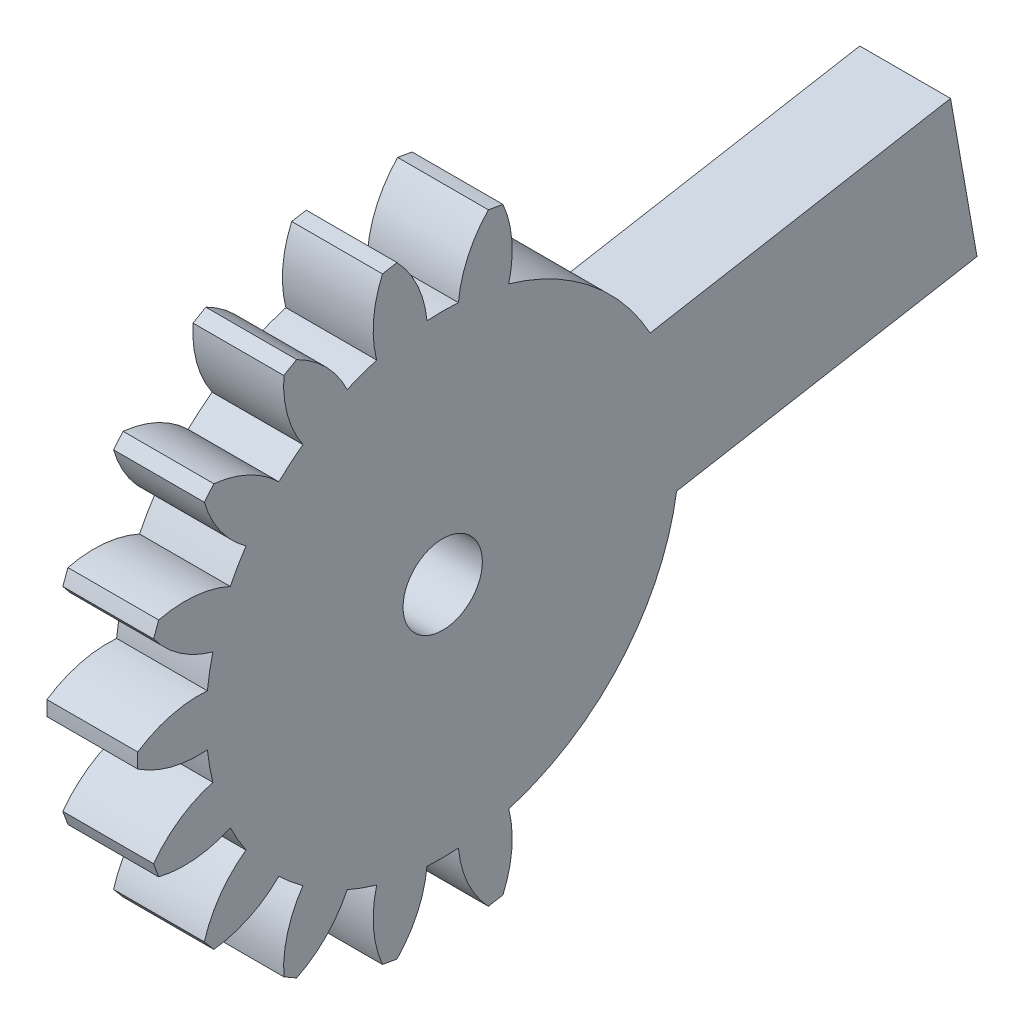
SolidWorks part; units mm, degrees
ref_plane "Plane1" through (0, 0, 0) normal (0, 0, 1) x (1, 0, 0)
ref_plane "Plane2" through (0, 0, 0) normal (0, 1, 0) x (1, 0, 0)
ref_plane "Plane3" through (0, 0, 0) normal (1, 0, 0) x (0, 0, -1)
sketch "HoldingSke" plane through (0, 0, 0) normal (0, 1, 0) x (1, 0, 0)
  line L0 (0, 0) -> (483.1367, -156.9806)
  line L1 (-15, 0) -> (100, 0) construction
  line L2 (0, 0) -> (-2.1039, 2.3779)
  line L3 (0, 0) -> (-11.863, 4.5341)
  line L4 (0, 0) -> (8.2133, 2.6687)
  line L5 (0, 0) -> (-47.5972, -17.7524)
  line L6 (0, 0) -> (-2.632, -1.7758)
  line L7 (-2.1039, 2.3779) -> (8.8308, 51.9871)
  line L8 (-76.2, 54.61) -> (-72.771, 54.61)
  line L9 (-71.009, 38.7566) -> (-53.1078, 45.2721)
  line L10 (-76.2, 71.12) -> (104.1128, 71.12)
  line L11 (0, 0) -> (-3.175, 0)
  line L12 (-76.2, 101.6) -> (-76.1492, 101.6)
  line L13 (24.9733, 27.94) -> (52.9518, 28.4284)
  line L14 (24.9733, 27.94) -> (25.0241, 27.9398)
  line L15 (24.9733, 27.94) -> (100.4021, 29.52)
  circle A0 centre (0, 0) radius 1.5875
  circle A1 centre (0, 0) radius 9.8552
  circle A2 centre (0, 0) radius 38.1
  circle A3 centre (0, 0) radius 1.5875
  dimension "MHD" = 19.7104
  dimension "Hub_dia" = 76.2
  dimension "Bore" = 3.175
  dimension "MBD" = 3.175
  dimension "Num_teeth" = 18
  dimension "Pitch_radius" = 180.3128
  dimension "Pitch" = 508
  dimension "Width" = 3.175
  dimension "Overall_len" = 50.8
  dimension "Show_teeth" = 18
  dimension "Thickness" = 3.175
  dimension "OAL" = 50.8001
  dimension "T_dim" = 3.429
  dimension "Ap" = 20
  dimension "H" = 19.05
  dimension "Backlash" = 0.0508
  dimension "Addendum_fac" = 1
  dimension "Dedendum_fac" = 1.2
  dimension "Clearance_fac" = 0.2
  dimension "Dedendum_add" = 0.0508
sketch "BasProSke" plane through (0, 0, 0) normal (0, 1, 0) x (1, 0, 0)
  line L0 (-10, 0) -> (60, 0) construction
  line L1 (0, 0) -> (0, 12.7)
  line L2 (0, 0) -> (3.175, 0)
  line L3 (3.175, 0) -> (3.175, 12.7)
  line L4 (3.175, 12.7) -> (0, 12.7)
  dimension "Diameter" = 25.4
  dimension "Thickness" = 3.175
revolve "Base-Revolve" add sketch "BasProSke" angle 360 about L0
sketch "TooCutSke" plane through (0, 0, 0) normal (1, 0, 0) x (0, 0, -1)
  line L1 (0, 0) -> (0, 107) construction
  line L2 (0, 0) -> (-1.085, 11.3784) construction
  line L3 (0, 0) -> (-3.9571, 22.4417) construction
  line L4 (-1.085, 11.3784) -> (-1.9785, 11.2208) construction
  arc A0 (0.6537, 9.8335) -> (-0.6537, 9.8335) centre (0, 0) ccw
  arc A1 (1.9234, 12.5792) -> (-1.9234, 12.5792) centre (0, 0) ccw
  circle A2 centre (0, 0) radius 11.43 construction
  circle A3 centre (0, 0) radius 10.7407 construction
  arc A4 (-0.6537, 9.8335) -> (-1.9234, 12.5792) centre (-5.2046, 9.3954) ccw
  arc A5 (1.9234, 12.5792) -> (0.6537, 9.8335) centre (5.2046, 9.3954) ccw
  dimension "Root_dia" = 19.7104
  dimension "Overcut_dia" = 25.4508
  dimension "Pitch_dia" = 22.86
  dimension "Base_dia" = 21.4814
  dimension "Flank_rad" = 4.572
  dimension "Half_ang" = 10
  dimension "Half_CT" = 0.9073
extrude "ToothCut" cut sketch "TooCutSke" along normal through all
fillet "Breaks" [suppressed] radius 0.0254
fillet "RootFillets" [suppressed] radius 0.3048
pattern_circular "TeethCuts" count 18 every 20 about axis through (-10, 0, 0) along (1, 0, 0) of "ToothCut", "RootFillets", "Breaks"
sketch "HubNeaOneSke" plane through (0, 0, 0) normal (-1, 0, 0) x (0, 0, 1)
  circle A0 centre (0, 0) radius 9.8552
  dimension "Diameter" = 19.7104
extrude "HubNearOne" [suppressed] add sketch "HubNeaOneSke" along normal blind 47.6251
sketch "HubNeaBotSke" plane through (0, 0, 0) normal (-1, 0, 0) x (0, 0, 1)
  circle A0 centre (0, 0) radius 9.8552
  dimension "Diameter" = 19.7104
extrude "HubNearBoth" [suppressed] add sketch "HubNeaBotSke" along normal blind 23.8125
ref_plane "FarPln" through (3.175, 0, 0) normal (1, 0, 0) x (0, 0, -1)
sketch "HubFarSke" plane through (3.175, 0, 0) normal (1, 0, 0) x (0, 0, -1)
  circle A0 centre (0, 0) radius 9.8552
  dimension "Diameter" = 19.7104
extrude "HubFar" [suppressed] add sketch "HubFarSke" along normal blind 23.8125
sketch "BorSke" plane through (0, 0, 0) normal (1, 0, 0) x (0, 0, -1)
  circle A0 centre (0, 0) radius 1.5875
  dimension "Diameter" = 3.175
extrude "Bore" cut sketch "BorSke" along normal mid plane 101.6001
sketch "KeySke" plane through (0, 0, 0) normal (1, 0, 0) x (0, 0, -1)
  line L0 (-0.127, 0) -> (-0.127, 1.8415)
  line L1 (-0.127, 1.8415) -> (0.127, 1.8415)
  line L2 (0.127, 1.8415) -> (0.127, 0)
  line L3 (0, 0) -> (0, 34) construction
  line L4 (-0.127, 0) -> (0.127, 0)
  dimension "Offset" = 1.8415
  dimension "Width" = 0.254
extrude "Keyway" [suppressed] cut sketch "KeySke" along normal mid plane 101.6001
pattern_circular "Keyway2" [suppressed] count 2 every 90 about axis through (-10, 0, 0) along (1, 0, 0)
sketch "Sketch3" plane through (0, 0, 0) normal (-1, 0, 0) x (0, 0, 1)
  line L0 (2.2053, 12.5071) -> (-2.2053, -12.5071) construction
  arc A0 (2.5076, 12.45) -> (1.9018, 12.5568) centre (0, 0) ccw construction
  arc A1 (-2.5076, -12.45) -> (-1.9018, -12.5568) centre (0, 0) ccw construction
sketch "Sketch7" plane through (0, 0, 0) normal (-1, 0, 0) x (0, 0, 1)
  line L0 (-8.6367, 4.7469) -> (-21.1437, 6.9522)
  line L1 (-2.8893, 9.4221) -> (-3.6524, 12.8049)
  line L3 (-3.1735, -9.3303) -> (-4.1021, -12.668)
  line L4 (-21.1437, 6.9522) -> (-22.2464, 0.6987)
  line L5 (-22.2464, 0.6987) -> (-9.7393, -1.5067)
  line L6 (2.2053, 12.5071) -> (-2.2053, -12.5071) construction
  line L8 (0.5606, -0.0988) -> (50.9626, -8.9861) construction
  circle A1 centre (0, 0) radius 9.8552 construction
  arc A2 (-3.1735, -9.3303) -> (-9.7393, -1.5067) centre (0, 0) cw
  circle A3 centre (0, 0) radius 13.3156 construction
  arc A4 (-3.6524, 12.8049) -> (-4.1021, -12.668) centre (0, 0) cw
  arc A5 (-2.8893, 9.4221) -> (-8.6367, 4.7469) centre (0, 0) ccw
  arc A6 (0.6537, 9.8335) -> (-0.6537, 9.8335) centre (0, 0) ccw construction
  circle A7 centre (0, 0) radius 1.5875 construction
  arc A8 (-2.749, 9.464) -> (-3.9775, 9.0169) centre (0, 0) ccw construction
  point P29 (-21.6951, 3.8254)
  dimension "D1" = 6.35
  dimension "D7" = 26.6313
  dimension "D2" = 12.7
  dimension "D3" = 84.453
extrude "Cut-Extrude-Thin1" cut sketch "Sketch7" against normal blind 5.08 and the other way blind 1 thin
sketch "Sketch8" plane through (0, 0, 0) normal (-1, 0, 0) x (0, 0, 1)
  line L0 (-21.1437, 6.9522) -> (-22.2464, 0.6987)
  line L1 (-21.1437, 6.9522) -> (-8.6367, 4.7469)
  line L2 (-22.2464, 0.6987) -> (-9.7393, -1.5067)
  line L3 (-8.6367, 4.7469) -> (-9.7393, -1.5067)
  arc A0 (-2.749, 9.464) -> (-8.8429, 4.3507) centre (0, 0) ccw construction
extrude "Boss-Extrude1" add sketch "Sketch8" against normal up to surface (3.175 mm away) up to face at (3.175, 0.2886, 2.9794)
sketch "Sketch9" plane through (0, 0, 0) normal (-1, 0, 0) x (0, 0, 1)
  circle A1 centre (0, 0) radius 1.651
  dimension "D1" = 3.302
extrude "Cut-Extrude2" cut sketch "Sketch9" against normal up to surface (3.175 mm away)
scale "Scale1" bodies to scale 113 scale about centroid uniform scaling no x scale factor 1 y scale factor 0.84 z scale factor 0.84
equation "' \"Pitch@HoldingSke\" = 4"
equation "' \"Num_teeth@HoldingSke\" = 12"
equation "' \"Ap@HoldingSke\" =  20"
equation "' \"Width@HoldingSke\" = 0.5"
equation "' \"Hub_dia@HoldingSke\"= 1"
equation "' \"Overall_len@HoldingSke\" = 1.0"
equation "' \"Bore@HoldingSke\" = 0.75"
equation "' \"T_dim@HoldingSke\" = 0.85"
equation "' \"Width@KeySke\" = 0.25"
equation "' \"Show_teeth@HoldingSke\" = 13"
equation "' \"Backlash@HoldingSke\" = 0.009"
equation "' \"Addendum_fac@HoldingSke\" = 1.0"
equation "' \"Dedendum_fac@HoldingSke\" = 1.25"
equation "' \"Dedendum_add@HoldingSke\" = 0.00005"
equation "' \"Clearance_fac@HoldingSke\" = 0.25"
equation "' \"Pitch@HoldingSke\" = 0.5"
equation "' \"Num_teeth@HoldingSke\" = 23"
equation "' \"Show_teeth@HoldingSke\" = 23"
equation "' \"Backlash@HoldingSke\" = 0.0375"
equation "\"Overcut_dia@TooCutSke\" = (\"Num_teeth@HoldingSke\" + 2 * \"Addendum_fac@HoldingSke\") / \"Pitch@HoldingSke\" + 0.002"
equation "\"Pitch_dia@TooCutSke\" = \"Num_teeth@HoldingSke\" / \"Pitch@HoldingSke\""
equation "\"Base_dia@TooCutSke\" = \"Num_teeth@HoldingSke\" / \"Pitch@HoldingSke\" * cos((\"Ap@HoldingSke\"  * 3.14159265 / 180))"
equation "\"Root_dia@TooCutSke\" = (\"Num_teeth@HoldingSke\" + 2) / \"Pitch@HoldingSke\" - 2 * (\"Addendum_fac@HoldingSke\" + \"Dedendum_fac@HoldingSke\") / \"Pitch@HoldingSke\" - \"Dedendum_add@HoldingSke\" * 2"
equation "\"Half_ang@TooCutSke\" = 180 / \"Num_teeth@HoldingSke\""
equation "\"Half_CT@TooCutSke\" = \"Num_teeth@HoldingSke\" / \"Pitch@HoldingSke\" * sin((3.14159265 / 2 / \"Num_teeth@HoldingSke\")) / 2 - 7 * \"Backlash@HoldingSke\" / 4"
equation "\"Flank_rad@TooCutSke\" = \"Num_teeth@HoldingSke\" / \"Pitch@HoldingSke\" / 5"
equation "\"Radius@RootFillets\" = \"Clearance_fac@HoldingSke\" / \"Pitch@HoldingSke\" + \"Dedendum_add@HoldingSke\""
equation "\"Break_rad@Breaks\" = 0.02 / \"Pitch@HoldingSke\""
equation "\"Thickness@HoldingSke\" = \"Width@HoldingSke\""
equation "\"OAL@HoldingSke\" = \"Thickness@HoldingSke\""
equation "\"MHD@HoldingSke\" = (\"Num_teeth@HoldingSke\" + 2) / \"Pitch@HoldingSke\" - 2 * (\"Addendum_fac@HoldingSke\" + \"Dedendum_fac@HoldingSke\")  / \"Pitch@HoldingSke\" - \"Dedendum_add@HoldingSke\" * 2"
equation "\"MBD@HoldingSke\" = (\"Num_teeth@HoldingSke\" + 2) / \"Pitch@HoldingSke\" - 2 * (\"Addendum_fac@HoldingSke\" + \"Dedendum_fac@HoldingSke\")  / \"Pitch@HoldingSke\" - \"Dedendum_add@HoldingSke\" * 2 - 0.002"
equation "\"MHD@HoldingSke\" = ((sgn( \"MHD@HoldingSke\" - \"Hub_dia@HoldingSke\" )-1)*( \"MHD@HoldingSke\" - \"Hub_dia@HoldingSke\" ))/-2+ \"Hub_dia@HoldingSke\""
equation "\"MBD@HoldingSke\" = ((sgn( \"MBD@HoldingSke\" - \"Bore@HoldingSke\" )-1)*( \"MBD@HoldingSke\" - \"Bore@HoldingSke\" ))/-2+ \"Bore@HoldingSke\""
equation "\"OAL@HoldingSke\" = ((sgn( \"OAL@HoldingSke\" - \"Overall_len@HoldingSke\" )+1)*( \"OAL@HoldingSke\" - \"Overall_len@HoldingSke\" ))/2 + \"Overall_len@HoldingSke\" + 0.000002"
equation "\"Num_teeth@TeethCuts\" = int( \"Show_teeth@HoldingSke\" ) + 1"
equation "\"Num_teeth@TeethCuts\" = ((sgn( \"Num_teeth@TeethCuts\" - \"Num_teeth@HoldingSke\" )-1)*( \"Num_teeth@TeethCuts\" - \"Num_teeth@HoldingSke\" ))/-2+ \"Num_teeth@HoldingSke\""
equation "\"Num_teeth@TeethCuts\" = ((sgn( \"Num_teeth@TeethCuts\" - 2.0)+1)*( \"Num_teeth@TeethCuts\" - 2.0))/2 +2.0"
equation "\"Angle@TeethCuts\" = 360.0 / \"Num_teeth@HoldingSke\""
equation "\"Diameter@BasProSke\" = (\"Num_teeth@HoldingSke\" + 2 * \"Addendum_fac@HoldingSke\") / \"Pitch@HoldingSke\""
equation "\"Thickness@BasProSke\"  = \"Thickness@HoldingSke\""
equation "' \"Fillet_rad@BasProSke\" =  \"Thickness@HoldingSke\" * 0.05"
equation "\"MHD@HoldingSke\" = ((sgn( \"MHD@HoldingSke\" - \"Root_dia@TooCutSke\" )-1)*( \"MHD@HoldingSke\" - \"Root_dia@TooCutSke\" ))/-2+ \"Root_dia@TooCutSke\""
equation "\"Diameter@HubNeaOneSke\" = \"MHD@HoldingSke\""
equation "\"Length@HubNearOne\" = \"OAL@HoldingSke\" - \"Thickness@BasProSke\""
equation "\"Diameter@HubNeaBotSke\" = \"MHD@HoldingSke\""
equation "\"Length@HubNearBoth\" = ( \"OAL@HoldingSke\" - \"Thickness@BasProSke\" ) / 2.0"
equation "\"Thickness@FarPln\" = \"Thickness@BasProSke\""
equation "\"Diameter@HubFarSke\" = \"MHD@HoldingSke\""
equation "\"Length@HubFar\" = ( \"OAL@HoldingSke\" - \"Thickness@BasProSke\" ) / 2.0"
equation "\"Diameter@BorSke\" = \"MBD@HoldingSke\""
equation "\"D1@Bore\" = \"OAL@HoldingSke\" * 2.0"
equation "\"D1@Keyway\" = \"OAL@HoldingSke\" * 2.0"
equation "\"Offset@KeySke\" = \"T_dim@HoldingSke\" - \"MBD@HoldingSke\" / 2.0"
